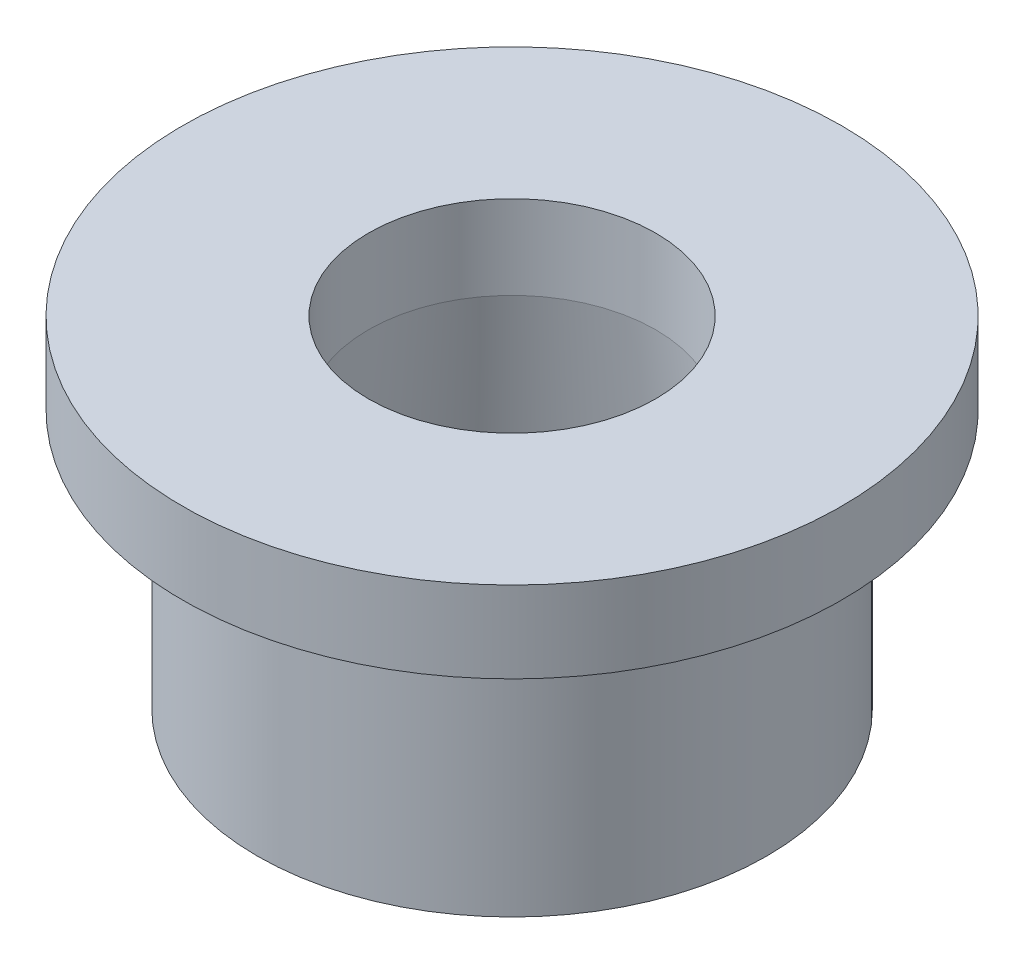
SolidWorks part; units mm, degrees
material "6061 Alloy"
ref_plane "Front Plane" through (0, 0, 0) normal (0, 0, 1) x (1, 0, 0)
ref_plane "Top Plane" through (0, 0, 0) normal (0, 1, 0) x (1, 0, 0)
ref_plane "Right Plane" through (0, 0, 0) normal (1, 0, 0) x (0, 0, -1)
sketch "Sketch1" plane through (0, 0, 0) normal (0, 0, 1) x (1, 0, 0)
  line L0 (0, 0) -> (0, 7.9756) construction
  line L1 (3.3655, 7.9756) -> (3.3655, 6.0138)
  line L2 (3.3655, 6.0138) -> (4.064, 0)
  line L3 (4.064, 0) -> (5.969, 0)
  line L4 (5.969, 0) -> (5.969, 4.9784)
  line L5 (5.969, 4.9784) -> (7.7216, 6.0706)
  line L6 (7.7216, 6.0706) -> (7.7216, 7.9756)
  line L7 (7.7216, 7.9756) -> (3.3655, 7.9756)
  dimension "D1" = 7.9756
  dimension "D2" = 6.731
  dimension "D3" = 15.4432
  dimension "D4" = 11.938
  dimension "D5" = 1.905
  dimension "D6" = 4.9784
  dimension "D7" = 8.128
revolve "Revolve1" add sketch "Sketch1" angle 360 about L0
